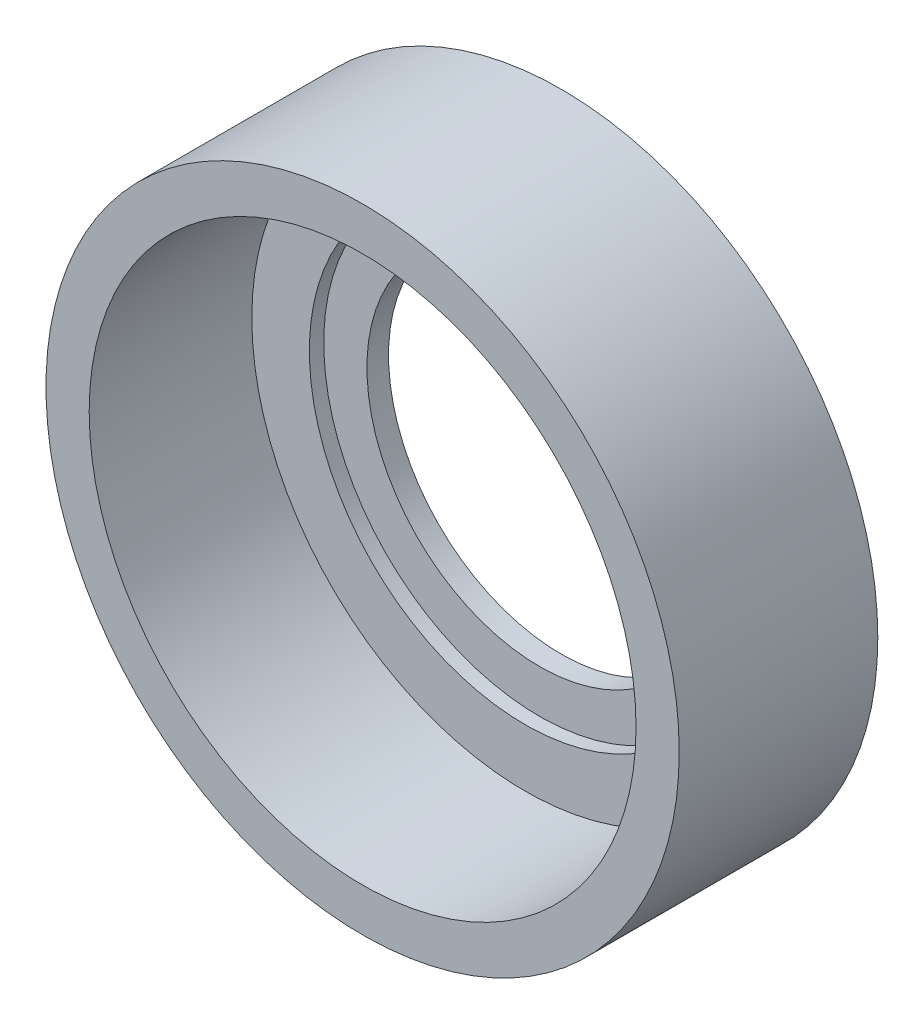
SolidWorks part; units mm, degrees
material "Zinc AC41A Alloy, As Cast"
ref_plane "Plan de face" through (0, 0, 0) normal (0, 0, 1) x (1, 0, 0)
ref_plane "Plan de dessus" through (0, 0, 0) normal (0, 1, 0) x (1, 0, 0)
ref_plane "Plan de droite" through (0, 0, 0) normal (1, 0, 0) x (0, 0, -1)
sketch "Sketch1" plane through (0, 0, 0) normal (0, 0, 1) x (1, 0, 0)
  circle A0 centre (0, 0) radius 6
  circle A1 centre (0, 0) radius 11
  dimension "D1" = 12
  dimension "D2" = 22
extrude "Boss-Extrude1" add sketch "Sketch1" along normal blind 0.75
sketch "Sketch2" plane through (0, 0, 0.75) normal (0, 0, 1) x (1, 0, 0)
  circle A0 centre (0, 0) radius 7.5
  circle A1 centre (0, 0) radius 11
  dimension "D1" = 15
  dimension "D2" = 22
extrude "Boss-Extrude2" add sketch "Sketch2" along normal blind 0.5
sketch "Sketch3" plane through (0, 0, 1.25) normal (0, 0, 1) x (1, 0, 0)
  circle A0 centre (0, 0) radius 9.5
  circle A1 centre (0, 0) radius 11
  dimension "D1" = 19
  dimension "D2" = 22
extrude "Boss-Extrude3" add sketch "Sketch3" along normal blind 5.65
